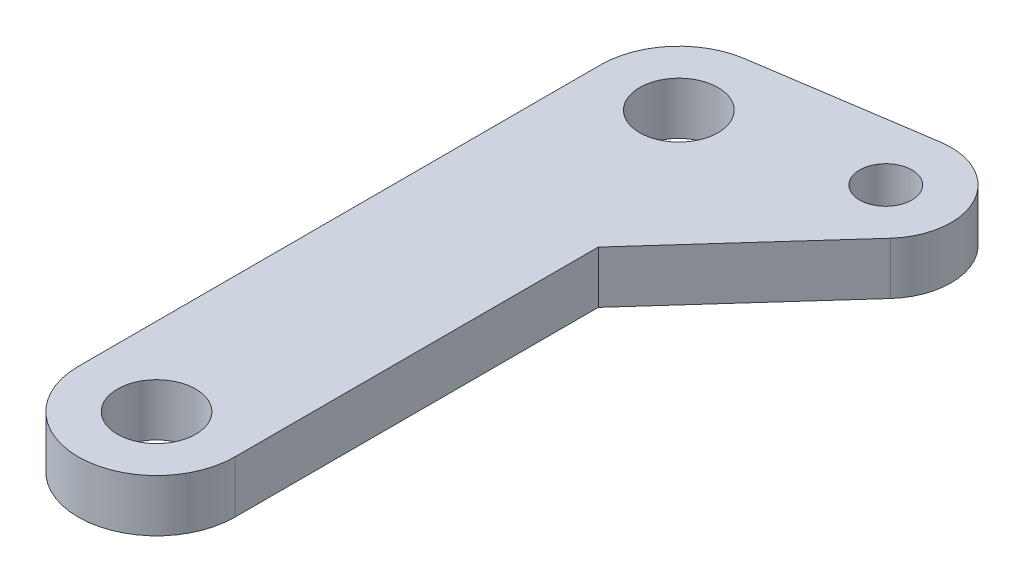
SolidWorks part; units mm, degrees
ref_plane "Front Plane" through (0, 0, 0) normal (0, 0, 1) x (1, 0, 0)
ref_plane "Top Plane" through (0, 0, 0) normal (0, 1, 0) x (1, 0, 0)
ref_plane "Right Plane" through (0, 0, 0) normal (1, 0, 0) x (0, 0, -1)
sketch "Sketch1" plane through (0, 0, 0) normal (0, 1, 0) x (1, 0, 0)
  line L0 (0, 0) -> (0, 20) construction
  line L1 (3, 0) -> (3, 20)
  line L2 (-3, 20) -> (-3, 0)
  circle A0 centre (0, 0) radius 1.5
  circle A1 centre (0, 20) radius 1.5
  arc A2 (3, 20) -> (-3, 20) centre (0, 20) ccw
  arc A3 (-3, 0) -> (3, 0) centre (0, 0) ccw
  dimension "D1" = 3
  dimension "D2" = 6
  dimension "D3" = 20
extrude "Boss-Extrude1" add sketch "Sketch1" along normal blind 2
sketch "Sketch2" plane through (0, 2, 0) normal (0, 1, 0) x (1, 0, 0)
  line L0 (8.3039, 19.8074) -> (3, 13.9145)
  line L1 (3, 0) -> (3, 20) construction
  line L2 (6.0721, 23.9517) -> (-0.4483, 22.9663)
  line L3 (3, 13.9145) -> (3, 20)
  circle A0 centre (6.4457, 21.4798) radius 1
  arc A1 (8.3039, 19.8074) -> (6.0721, 23.9517) centre (6.4457, 21.4798) ccw
  arc A2 (3, 20) -> (-3, 20) centre (0, 20) ccw construction
  arc A3 (3, 20) -> (-0.4483, 22.9663) centre (0, 20) ccw
  point P2 (9.4537, 21.6279)
  point P8 (5.1109, 21.6279)
  point P12 (6.3709, 21.6559)
  dimension "D1" = 2
  dimension "D2" = 2.5
extrude "Boss-Extrude2" add sketch "Sketch2" against normal up to surface (2 mm away) up to face at (0, 0, -10)
